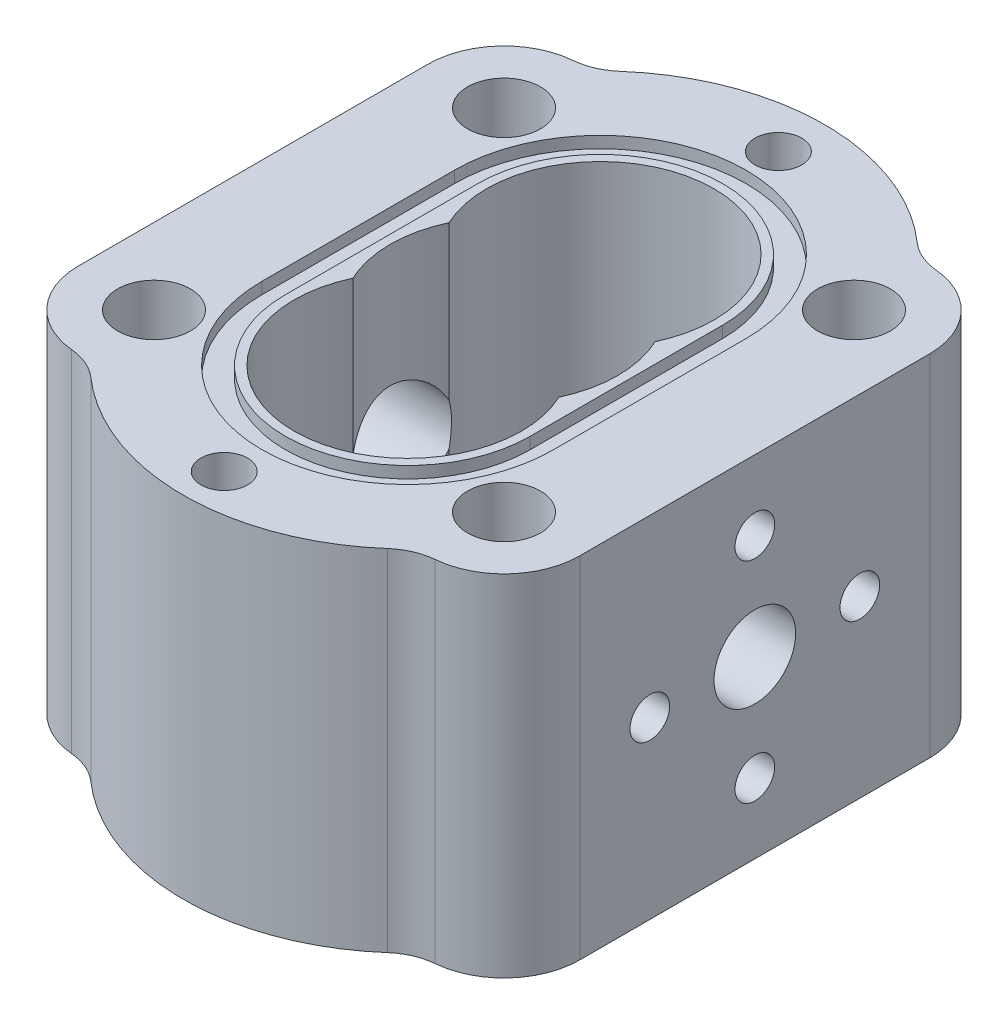
SolidWorks part; units mm, degrees
ref_plane "前视基准面" through (0, 0, 0) normal (0, 0, 1) x (1, 0, 0)
ref_plane "上视基准面" through (0, 0, 0) normal (0, 1, 0) x (1, 0, 0)
ref_plane "右视基准面" through (0, 0, 0) normal (1, 0, 0) x (0, 0, -1)
sketch "草图1" plane through (0, 0, 0) normal (0, 1, 0) x (1, 0, 0)
  line L0 (0, 16.5) -> (0, -16.5) construction
  line L3 (38.5, 16.5) -> (38.5, -16.5)
  line L4 (-38.5, 16.5) -> (-38.5, -16.5)
  line L7 (-30, -30) -> (-30, 30) construction
  line L8 (-43, -30) -> (-43, 30)
  line L9 (-17, -30) -> (-17, 30)
  line L10 (0, 0) -> (-30, 0) construction
  line L11 (0, -55) -> (0, 55) construction
  line L12 (30, -30) -> (30, 30) construction
  line L13 (43, -30) -> (43, 30)
  line L14 (17, -30) -> (17, 30)
  arc A6 (38.5, 16.5) -> (-38.5, 16.5) centre (0, 16.5) ccw
  arc A7 (-38.5, -16.5) -> (38.5, -16.5) centre (0, -16.5) ccw
  arc A8 (-43, -30) -> (-17, -30) centre (-30, -30) ccw
  arc A9 (-17, 30) -> (-43, 30) centre (-30, 30) ccw
  arc A10 (43, -30) -> (17, -30) centre (30, -30) cw
  arc A11 (17, 30) -> (43, 30) centre (30, 30) cw
  point P2 (0, 0)
  point P9 (-30, 0)
  point P20 (30, 0)
  dimension "D5" = 110
  dimension "D1" = 38.5
  dimension "D2" = 30
  dimension "D3" = 86
  dimension "D4" = 60
extrude "凸台-拉伸1" add sketch "草图1" along normal blind 60 contours A6 A9 L8 A8 A7 L4 | L9 A9 A6 L4 A7 A8 | L14 A11 A6 A9 L9 A8 A7 A10 | A11 L14 A10 A7 L3 A6 | A11 A6 L3 A7 A10 L13
fillet "圆角1" radius 10 4 edges at (-28.0652, 30, -42.8552) (28.0652, 30, -42.8552) (-28.0652, 30, 42.8552) (28.0652, 30, 42.8552)
sketch "草图2" plane through (0, 60, 0) normal (0, 1, 0) x (1, 0, 0)
  line L0 (0, 0) -> (-43, 0) construction
  line L1 (-43, -30) -> (-43, 30) construction
  line L2 (0, 0) -> (0, 55) construction
  circle A0 centre (-30, 30) radius 6.25
  arc A1 (25.4345, 45.4022) -> (-25.4345, 45.4022) centre (0, 16.5) ccw construction
  circle A2 centre (30, 30) radius 6.25
  circle A3 centre (30, -30) radius 6.25
  circle A4 centre (-30, -30) radius 6.25
  dimension "D1" = 12.5
  dimension "D2" = 60
  dimension "D3" = 60
extrude "切除-拉伸1" cut sketch "草图2" against normal through all both and the other way through all
sketch "草图3" plane through (0, 60, 0) normal (0, 1, 0) x (1, 0, 0)
  line L0 (0, 16.5) -> (0, -16.5) construction
  circle A0 centre (0, 16.5) radius 19.5
  circle A1 centre (0, -16.5) radius 19.5
  circle A2 centre (0, 0) radius 19.5
  point P7 (0, 22.3638)
  dimension "D1" = 39
  dimension "D2" = 33
extrude "切除-拉伸2" cut sketch "草图3" against normal through all both and the other way through all
sketch "草图4" plane through (0, 60, 0) normal (0, 1, 0) x (1, 0, 0)
  line L0 (0, 16.5) -> (0, -16.5) construction
  line L1 (21, 16.5) -> (21, -16.5)
  line L2 (-21, 16.5) -> (-21, -16.5)
  line L3 (25, 16.5) -> (25, -16.5)
  line L4 (-25, 16.5) -> (-25, -16.5)
  arc A0 (21, 16.5) -> (-21, 16.5) centre (0, 16.5) ccw
  arc A1 (-21, -16.5) -> (21, -16.5) centre (0, -16.5) ccw
  arc A2 (25.4345, 45.4022) -> (-25.4345, 45.4022) centre (0, 16.5) ccw construction
  arc A3 (-25, -16.5) -> (25, -16.5) centre (0, -16.5) ccw
  arc A4 (25, 16.5) -> (-25, 16.5) centre (0, 16.5) ccw
  point P3 (0, 0)
  point P11 (0, -17.36)
  dimension "D1" = 21
  dimension "D2" = 4
extrude "切除-拉伸3" cut sketch "草图4" against normal blind 2
ref_plane "基准面1" through (0, 30, 0) normal (0, 1, 0) x (1, 0, 0)
mirror "镜向1" about plane through (0, 30, 0) normal (0, 1, 0) of "切除-拉伸3"
sketch "草图6" plane through (0, 60, 0) normal (0, 1, 0) x (1, 0, 0)
  line L0 (0, -47.9647) -> (0, 47.0353) construction
  dimension "D1" = 95
hole_wizard "大小mm 暗销孔1" positions "3D草图1" profile "草图7" hole size "Ø8.0" standard "GB"
sketch3d "3D草图1"
  point P0 (0, 60, -47.0353)
  point P3 (0, 60, 47.9647)
sketch "草图7" plane through (0, 60, -47.0353) normal (1, 0, 0) x (0, 0, 1)
  line L0 (0, 0) -> (0, 8.4034)
  line L1 (0, 8.4034) -> (4, 6)
  line L2 (4, 6) -> (4, 0)
  line L5 (4, 0) -> (0, 0)
  line L10 (0, 8.4034) -> (-4, 6) construction
  line L11 (0, -6.35) -> (0, 107.95) construction
  dimension "孔直径" = 8
  dimension "孔深度" = 6
  dimension "导头角度" = 118
sketch "草图9" plane through (43, 0, 0) normal (1, 0, 0) x (0, 0, -1)
  line L0 (-0.4647, 60) -> (0, 0) construction
  line L1 (-47.9647, 60) -> (47.0353, 60) construction
  circle A0 centre (-0.2324, 30) radius 18 construction
  circle A1 centre (0, 30) radius 7
  dimension "D1" = 36
  dimension "D2" = 14
extrude "切除-拉伸4" cut sketch "草图9" against normal up to next and the other way through all
sketch "草图10" plane through (-43, 0, 0) normal (-1, 0, 0) x (0, 0, 1)
  circle A0 centre (0, 30) radius 7 construction
  circle A1 centre (0, 30) radius 7 construction
  circle A2 centre (0, 30) radius 9
  dimension "D1" = 2
extrude "切除-拉伸5" cut sketch "草图10" against normal up to next
sketch "草图11" plane through (43, 0, 0) normal (1, 0, 0) x (0, 0, -1)
  line L0 (0, 0) -> (0, 12) construction
  line L1 (0, 48) -> (0, 12) construction
  line L2 (18, 30) -> (-18, 30) construction
  circle A0 centre (0, 30) radius 18 construction
  dimension "D1" = 36
hole_wizard "M8 螺纹孔2" positions "3D草图3" profile "草图13" tap size "M8" standard "GB"
sketch3d "3D草图3"
  point P0 (43, 48, 0)
  point P3 (43, 30, -18)
  point P6 (43, 12, 0)
  point P9 (43, 30, 18)
sketch "草图13" plane through (43, 48, 0) normal (0, 1, 0) x (0, 0, -1)
  line L0 (0, 0) -> (0, 17.0429)
  line L1 (0, 17.0429) -> (3.4, 15)
  line L2 (3.4, 15) -> (3.4, 0)
  line L5 (3.4, 0) -> (0, 0)
  line L10 (0, 17.0429) -> (-3.4, 15) construction
  line L11 (0, -6.35) -> (0, 107.95) construction
  dimension "螺纹孔钻头直径" = 6.8
  dimension "螺纹孔钻头深度" = 15
  dimension "导头角度" = 118
cosmetic thread "孔螺蚊线2" parameters "D1"=15, "D2"=8
cosmetic thread "孔螺蚊线3" parameters "D1"=15, "D2"=8
cosmetic thread "孔螺蚊线4" parameters "D1"=15, "D2"=8
cosmetic thread "孔螺蚊线5" parameters "D1"=15, "D2"=8
mirror "镜向2" about plane through (0, 0, 0) normal (1, 0, 0) of "M8 螺纹孔2"
